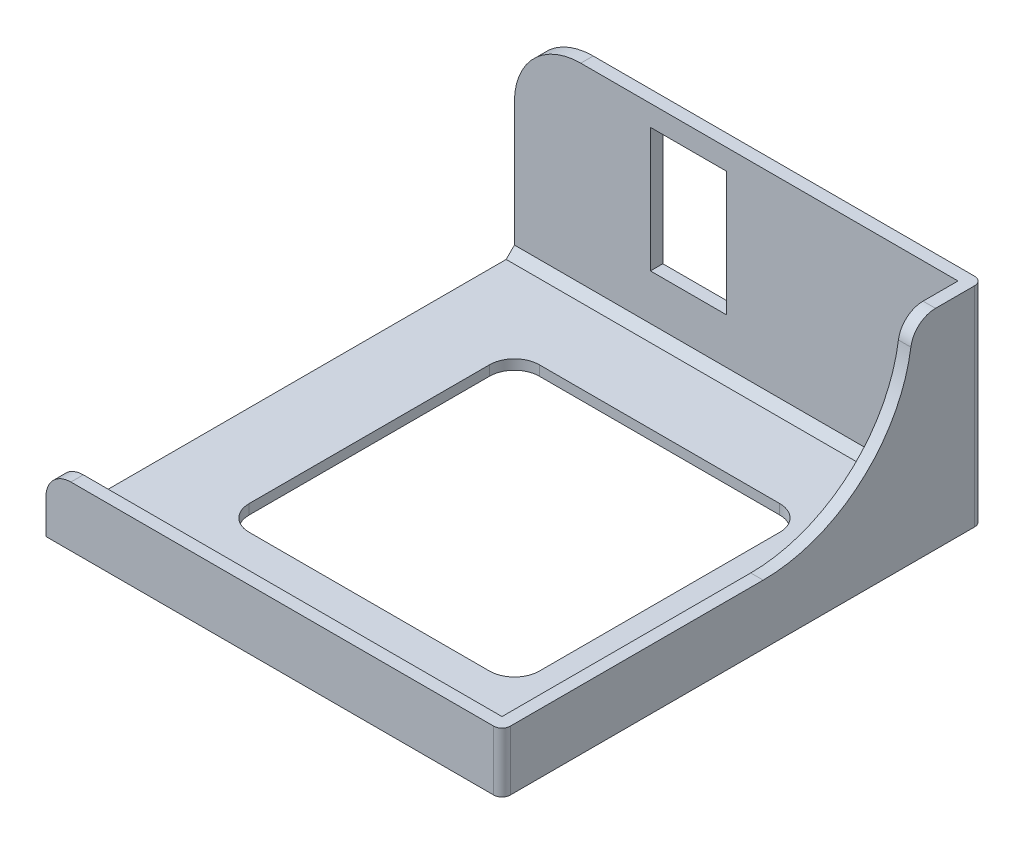
SolidWorks part; units mm, degrees
ref_plane "Plano frontal" through (0, 0, 0) normal (0, 0, 1) x (1, 0, 0)
ref_plane "Plano superior" through (0, 0, 0) normal (0, 1, 0) x (1, 0, 0)
ref_plane "Plano direito" through (0, 0, 0) normal (1, 0, 0) x (0, 0, -1)
sketch "Esboço1" plane through (0, 0, 0) normal (0, 1, 0) x (1, 0, 0)
  line L1 (-27.5, -29) -> (27.5, -29)
  line L2 (-27.5, -29) -> (-27.5, 29)
  line L3 (-27.5, 29) -> (27.5, 29)
  line L4 (27.5, -29) -> (27.5, 29)
  line L5 (-27.5, -29) -> (27.5, 29) construction
  line L6 (-27.5, 29) -> (27.5, -29) construction
  point P0 (0, 0)
  dimension "D1" = 55
  dimension "D2" = 58
extrude "Base" add sketch "Esboço1" along normal blind 1.2
sketch "Esboço2" plane through (0, 1.2, 0) normal (0, 1, 0) x (1, 0, 0)
  line L0 (-27.5, 29) -> (-27.5, -29) construction
  line L1 (-27.5, -29) -> (27.5, -29) construction
  line L2 (27.5, -29) -> (27.5, 29) construction
  line L3 (27.5, 29) -> (-27.5, 29) construction
  line L4 (-27.5, 29) -> (-27.5, -29)
  line L5 (-27.5, -29) -> (27.5, -29)
  line L6 (27.5, -29) -> (27.5, 29)
  line L7 (27.5, 29) -> (-27.5, 29)
  line L8 (26, 27.5) -> (-26, 27.5)
  line L9 (-26, 27.5) -> (-26, -27.5)
  line L10 (-26, -27.5) -> (26, -27.5)
  line L11 (26, -27.5) -> (26, 27.5)
  dimension "D1" = 1.5
extrude "Paredes" add sketch "Esboço2" along normal blind 24
sketch "Esboço3" plane through (0, 25.2, 0) normal (0, 1, 0) x (1, 0, 0)
  line L0 (-27.5, 29) -> (-27.5, -29) construction
  line L1 (-29.986, -27.5) -> (-25.014, -27.5)
  line L2 (-29.986, -27.5) -> (-29.986, 27.5)
  line L3 (-29.986, 27.5) -> (-25.014, 27.5)
  line L4 (-25.014, -27.5) -> (-25.014, 27.5)
  line L5 (-29.986, -27.5) -> (-25.014, 27.5) construction
  line L6 (-29.986, 27.5) -> (-25.014, -27.5) construction
  line L7 (26, 27.5) -> (-26, 27.5) construction
  point P0 (-27.5, 0)
extrude "Corte-extrusão1" cut sketch "Esboço3" against normal up to surface (24 mm away) up to face at (0, 1.2, 0)
sketch "Esboço4" plane through (0, 0, -29) normal (0, 0, -1) x (-1, 0, 0)
  line L0 (-27.5, 25.2) -> (-27.5, 0) construction
  line L1 (1.9, 7.7) -> (11.1, 7.7)
  line L2 (1.9, 7.7) -> (1.9, 22.7)
  line L3 (1.9, 22.7) -> (11.1, 22.7)
  line L4 (11.1, 7.7) -> (11.1, 22.7)
  line L5 (1.9, 7.7) -> (11.1, 22.7) construction
  line L6 (1.9, 22.7) -> (11.1, 7.7) construction
  line L7 (-27.5, 0) -> (27.5, 0) construction
  point P0 (6.5, 15.2)
  point P7 (0, 0)
  point P9 (-27.4596, 0)
  point P12 (13.0775, -1.2344)
  dimension "D1" = 9.2
  dimension "D2" = 15
  dimension "D3" = 34
  dimension "D4" = 15.2
extrude "Encaixe chave" cut sketch "Esboço4" against normal blind 17
sketch "Esboço5" plane through (-27.5, 0, 0) normal (-1, 0, 0) x (0, 0, 1)
  line L0 (29, 25.2) -> (29, 0) construction
  line L1 (27.5, 25.2) -> (29, 25.2)
  line L2 (27.5, 25.2) -> (27.5, 7.2)
  line L3 (27.5, 7.2) -> (29, 7.2)
  line L4 (29, 25.2) -> (29, 7.2)
  dimension "D1" = 18
extrude "Corte-extrusão3" cut sketch "Esboço5" against normal through all
sketch "Esboço6" plane through (27.5, 0, 0) normal (1, 0, 0) x (0, 0, -1)
  line L0 (-27.5, 25.2) -> (29, 25.2) construction
  line L1 (-27.5, 25.2) -> (2.5, 25.2)
  line L2 (-27.5, 25.2) -> (-27.5, 7.2)
  line L3 (-27.5, 7.2) -> (2.5, 7.2)
  line L4 (2.5, 25.2) -> (2.5, 7.2)
  line L5 (20.5, 25.2) -> (2.5, 25.2)
  arc A0 (2.5, 7.2) -> (20.5, 25.2) centre (2.5, 25.2) ccw
  line M2 (29, 25.2) -> (-27.5, 25.2)
  line M3 (-27.5, 25.2) -> (-27.5, 7.2)
  dimension "D1" = 18
  dimension "D2" = 30
extrude "Corte-extrusão4" cut sketch "Esboço6" against normal blind 17 contours L4 A0 M2 | L4 L3 M2 M3
fillet "Filete1" radius 8 1 edges at (-27.5, 25.2, -28.25)
fillet "Filete2" radius 3 1 edges at (-27.5, 7.2, 28.25)
fillet "Filete3" radius 3 1 edges at (26.75, 25.2, -20.5)
fillet "Filete4" radius 1 1 edges at (27.5, 3.6, 29)
fillet "Filete5" radius 1 1 edges at (27.5, 12.6, -29)
chamfer "Chanfro1" distance 1 angle 45 3 edges at (-0.75, 1.2, 27.5) (26, 1.2, 0) (-0.75, 1.2, -27.5)
sketch "Esboço7" plane through (0, 1.2, 0) normal (0, 1, 0) x (1, 0, 0)
  line L1 (-14.5, -17.5) -> (14.5, -17.5)
  line L2 (-17.5, -14.5) -> (-17.5, 14.5)
  line L3 (-14.5, 17.5) -> (14.5, 17.5)
  line L4 (17.5, -14.5) -> (17.5, 14.5)
  line L5 (-17.5, -17.5) -> (17.5, 17.5) construction
  line L6 (-17.5, 17.5) -> (17.5, -17.5) construction
  arc A0 (14.5, 17.5) -> (17.5, 14.5) centre (14.5, 14.5) cw
  arc A1 (17.5, -14.5) -> (14.5, -17.5) centre (14.5, -14.5) cw
  arc A2 (-14.5, -17.5) -> (-17.5, -14.5) centre (-14.5, -14.5) cw
  arc A3 (-14.5, 17.5) -> (-17.5, 14.5) centre (-14.5, 14.5) ccw
  point P0 (0, 0)
  dimension "D3" = 3
  dimension "D1" = 35
  dimension "D2" = 35
extrude "Corte-extrusão5" cut sketch "Esboço7" against normal blind 17
